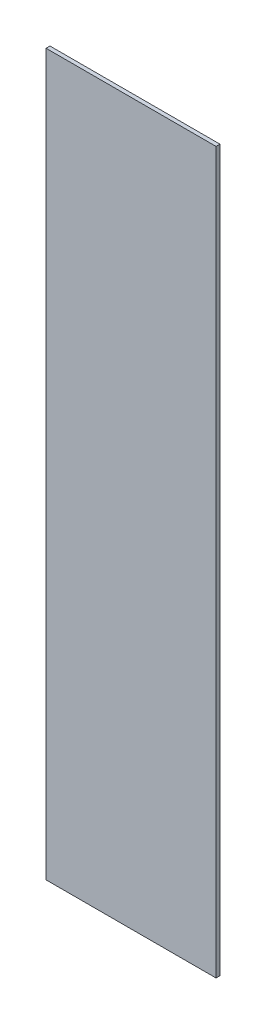
SolidWorks part; units mm, degrees
ref_plane "Plan de face" through (0, 0, 0) normal (0, 0, 1) x (1, 0, 0)
ref_plane "Plan de dessus" through (0, 0, 0) normal (0, 1, 0) x (1, 0, 0)
ref_plane "Plan de droite" through (0, 0, 0) normal (1, 0, 0) x (0, 0, -1)
sketch "Esquisse1" plane through (0, 0, 0) normal (0, 0, 1) x (1, 0, 0)
  line L1 (-216.75, -918.5) -> (216.75, -918.5)
  line L2 (-216.75, -918.5) -> (-216.75, 918.5)
  line L3 (-216.75, 918.5) -> (216.75, 918.5)
  line L4 (216.75, -918.5) -> (216.75, 918.5)
  line L5 (-216.75, -918.5) -> (216.75, 918.5) construction
  line L6 (-216.75, 918.5) -> (216.75, -918.5) construction
  point P0 (0, 0)
  dimension "D1" = 433.5
  dimension "D2" = 1837
extrude "Boss.-Extru.1" add sketch "Esquisse1" along normal blind 10
